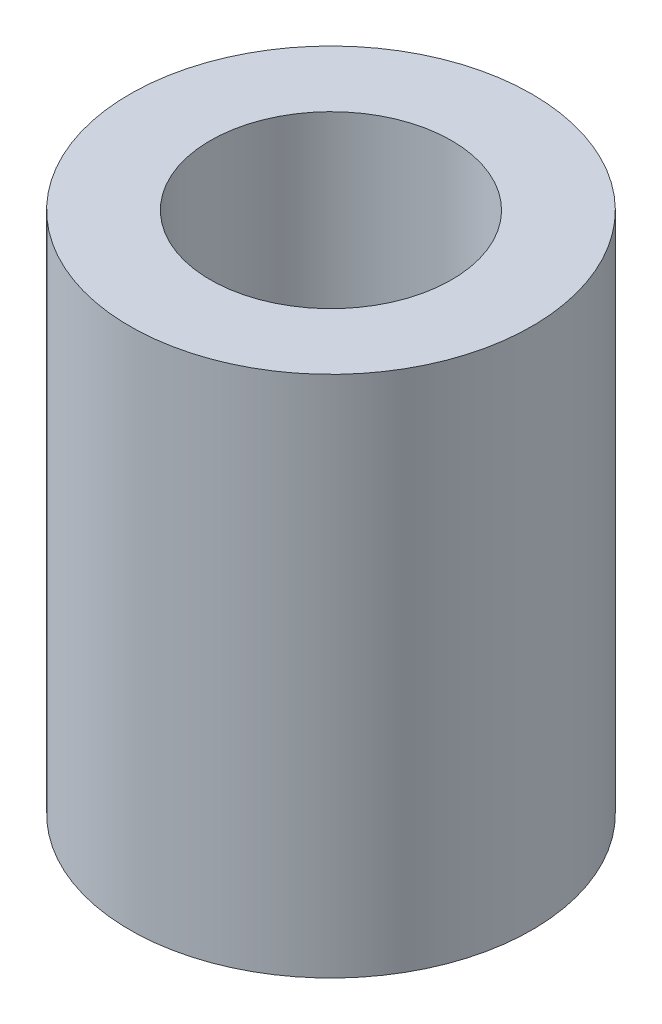
SolidWorks part; units mm, degrees
material "1060 Alloy"
ref_plane "Front Plane" through (0, 0, 0) normal (0, 0, 1) x (1, 0, 0)
ref_plane "Top Plane" through (0, 0, 0) normal (0, 1, 0) x (1, 0, 0)
ref_plane "Right Plane" through (0, 0, 0) normal (1, 0, 0) x (0, 0, -1)
sketch "Sketch1" plane through (0, 0, 0) normal (0, 1, 0) x (1, 0, 0)
  circle A0 centre (0, 0) radius 3
  circle A1 centre (0, 0) radius 5
extrude "Boss-Extrude1" add sketch "Sketch1" along normal blind 13
